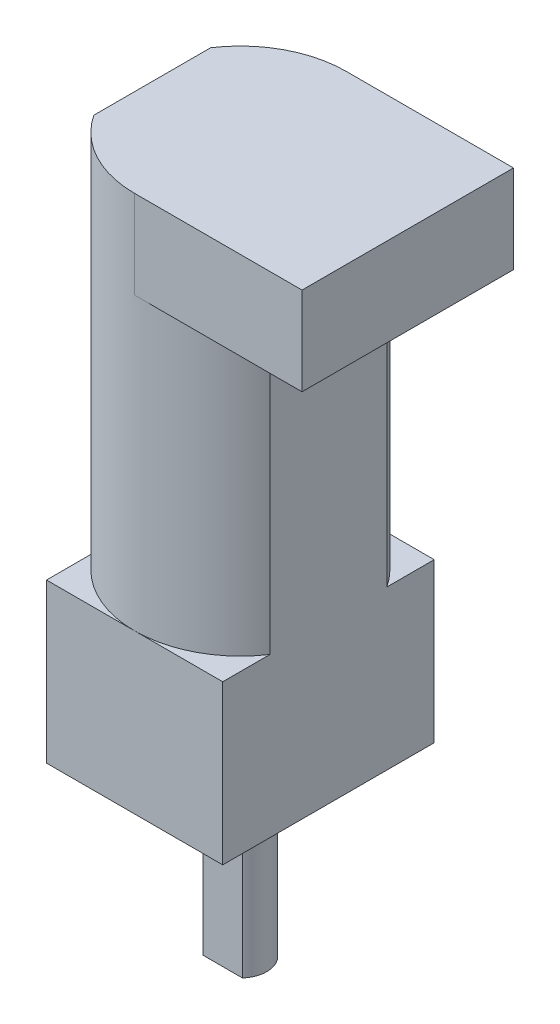
SolidWorks part; units mm, degrees
ref_plane "前视基准面" through (0, 0, 0) normal (0, 0, 1) x (1, 0, 0)
ref_plane "上视基准面" through (0, 0, 0) normal (0, 1, 0) x (1, 0, 0)
ref_plane "右视基准面" through (0, 0, 0) normal (1, 0, 0) x (0, 0, -1)
other "Configuration Table"
sketch "草图1" plane through (0, 0, 0) normal (0, 1, 0) x (1, 0, 0)
  line L0 (-5, -3.3166) -> (-5, 3.3166)
  line L1 (5, -3.3166) -> (5, 3.3166)
  line L2 (0, 6) -> (0, -6) construction
  arc A0 (-5, -3.3166) -> (5, -3.3166) centre (0, 0) ccw
  arc A1 (5, 3.3166) -> (-5, 3.3166) centre (0, 0) ccw
  dimension "D2" = 12
  dimension "D1" = 10
extrude "凸台-拉伸1" add sketch "草图1" along normal blind 21.5
sketch "草图2" plane through (0, 21.5, 0) normal (0, 1, 0) x (1, 0, 0)
  line L0 (-5, 3.3166) -> (-5, -3.3166) construction
  line L1 (0, 6) -> (9.5, 6)
  line L2 (0, 6) -> (0, -6)
  line L3 (0, -6) -> (9.5, -6)
  line L4 (9.5, 6) -> (9.5, -6)
  line L5 (0, 6) -> (9.5, -6) construction
  line L6 (0, -6) -> (9.5, 6) construction
  arc A0 (5, 3.3166) -> (-5, 3.3166) centre (0, 0) ccw construction
  arc A1 (-5, -3.3166) -> (5, -3.3166) centre (0, 0) ccw construction
  point P4 (4.75, 0)
  dimension "D1" = 14.5
extrude "凸台-拉伸2" add sketch "草图2" against normal blind 5
sketch "草图3" plane through (0, 0, 0) normal (0, -1, 0) x (1, 0, 0)
  line L0 (5, 3.3166) -> (5, -3.3166) construction
  line L1 (-5, -6) -> (5, -6)
  line L2 (-5, -6) -> (-5, 6)
  line L3 (-5, 6) -> (5, 6)
  line L4 (5, -6) -> (5, 6)
  line L5 (-5, -6) -> (5, 6) construction
  line L6 (-5, 6) -> (5, -6) construction
  line L7 (-5, -3.3166) -> (-5, 3.3166) construction
  arc A0 (5, 3.3166) -> (-5, 3.3166) centre (0, 0) ccw construction
  point P4 (0, 0)
extrude "凸台-拉伸3" add sketch "草图3" along normal blind 9
sketch "草图4" plane through (0, -9, 0) normal (0, -1, 0) x (1, 0, 0)
  circle A0 centre (0, 0) radius 2
  dimension "D1" = 4
extrude "凸台-拉伸4" add sketch "草图4" along normal blind 0.7
sketch "草图5" plane through (0, -9.7, 0) normal (0, -1, 0) x (1, 0, 0)
  line L0 (-1.118, 1) -> (1.118, 1)
  arc A0 (-1.118, 1) -> (1.118, 1) centre (0, 0) ccw
  dimension "D2" = 3
  dimension "D1" = 1
extrude "凸台-拉伸6" add sketch "草图5" along normal offset from surface (9.3 mm away) 10 up to face at (0, -9, -2) offset beyond the face yes
